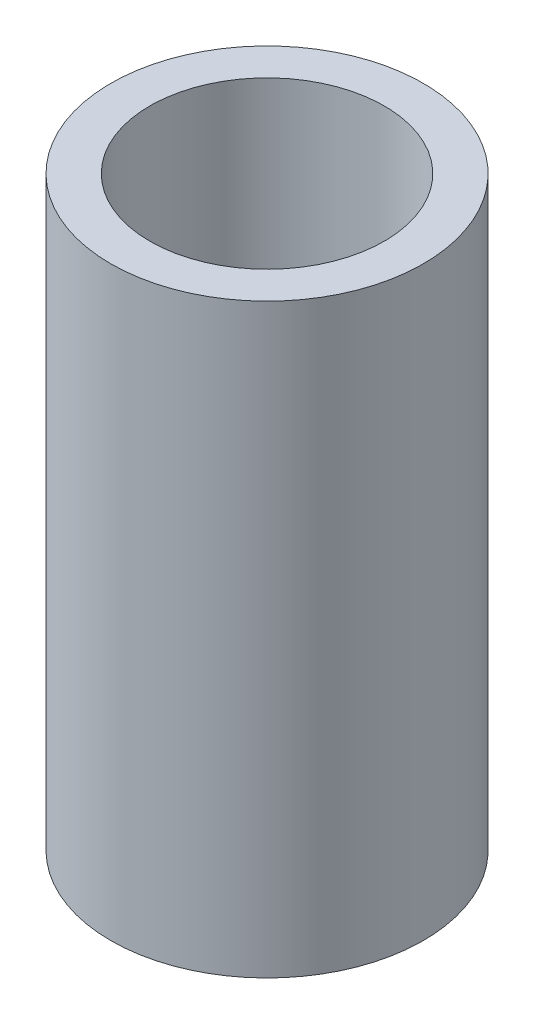
SolidWorks part; units mm, degrees
ref_plane "前视基准面" through (0, 0, 0) normal (0, 0, 1) x (1, 0, 0)
ref_plane "上视基准面" through (0, 0, 0) normal (0, 1, 0) x (1, 0, 0)
ref_plane "右视基准面" through (0, 0, 0) normal (1, 0, 0) x (0, 0, -1)
sketch "草图1" plane through (0, 0, 0) normal (0, 1, 0) x (1, 0, 0)
  circle A0 centre (0, 0) radius 3
  circle A1 centre (0, 0) radius 4
  dimension "D1" = 6
  dimension "8" = 8
extrude "凸台-拉伸1" add sketch "草图1" along normal blind 15
